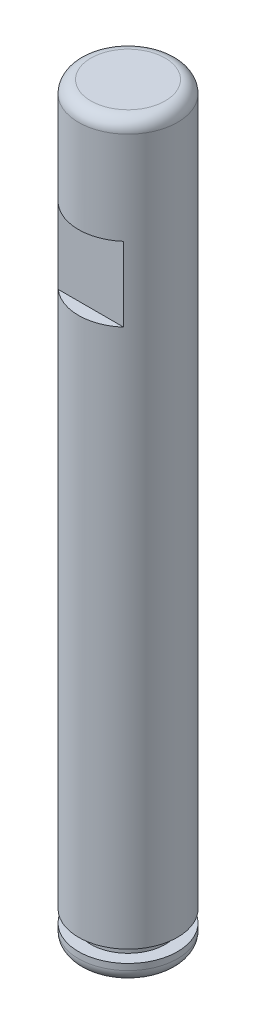
SolidWorks part; units mm, degrees
ref_plane "Front Plane" through (0, 0, 0) normal (0, 0, 1) x (1, 0, 0)
ref_plane "Top Plane" through (0, 0, 0) normal (0, 1, 0) x (1, 0, 0)
ref_plane "Right Plane" through (0, 0, 0) normal (1, 0, 0) x (0, 0, -1)
sketch "Sketch1" plane through (0, 0, 0) normal (0, 0, 1) x (1, 0, 0)
  line L0 (0, 0) -> (0, 31.0873) construction
  line L2 (0, 0) -> (-2, 0)
  line L3 (0, 0) -> (0, 30.25)
  line L4 (0, 30.25) -> (-2, 30.25)
  line L5 (-2, 0) -> (-2, 30.25)
  line L6 (-2, 1.25) -> (-1.5, 1.25)
  line L7 (-2, 1.25) -> (-2, 0.75)
  line L8 (-2, 0.75) -> (-1.5, 0.75)
  line L9 (-1.5, 1.25) -> (-1.5, 0.75)
  dimension "D1" = 30.25
  dimension "D2" = 4
  dimension "D3" = 3
  dimension "D4" = 0.75
  dimension "D5" = 0.5
revolve "Revolve1" add sketch "Sketch1" angle 360 about L0
fillet "Fillet1" radius 0.5 2 edges at (0, 30.25, -2) (0, 0, -2)
sketch "Sketch2" plane through (0, 0, 0) normal (0, 0, 1) x (1, 0, 0)
  line L0 (-2, 29.75) -> (-2, 1.25) construction
  line L1 (-2, 26) -> (2, 26)
  line L2 (-2, 26) -> (-2, 23)
  line L3 (-2, 23) -> (2, 23)
  line L4 (2, 26) -> (2, 23)
  line L5 (2, 1.25) -> (2, 29.75) construction
  line L6 (1.5, 30.25) -> (-1.5, 30.25) construction
  dimension "D1" = 3
  dimension "D2" = 4.25
extrude "Cut-Extrude1" cut sketch "Sketch2" along normal through all from offset 1.5
